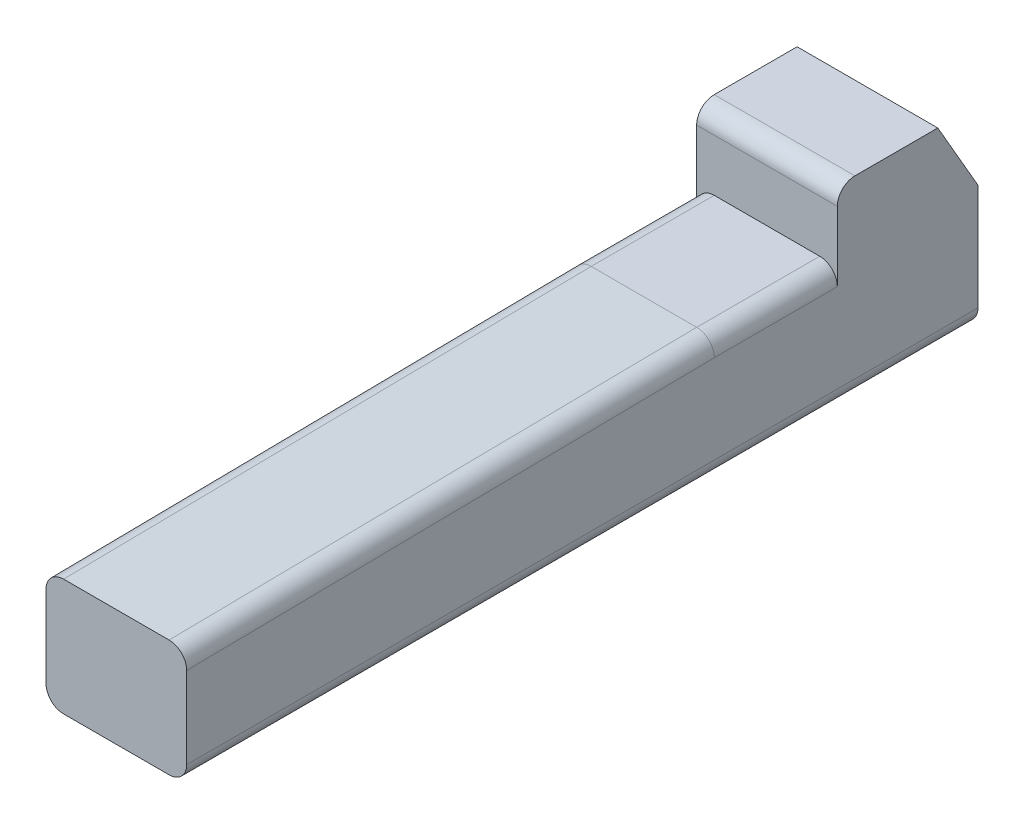
SolidWorks part; units mm, degrees
ref_plane "Front Plane" through (0, 0, 0) normal (0, 0, 1) x (1, 0, 0)
ref_plane "Top Plane" through (0, 0, 0) normal (0, 1, 0) x (1, 0, 0)
ref_plane "Right Plane" through (0, 0, 0) normal (1, 0, 0) x (0, 0, -1)
sketch "Sketch1" plane through (0, 0, 0) normal (0, 0, 1) x (1, 0, 0)
  line L0 (0, 0) -> (0, 4806.0835) construction
  line L1 (0, 0) -> (4806.0835, 0) construction
  line L3 (-4, -5.5) -> (4, -5.5)
  line L4 (-4, -5.5) -> (-4, 5.5)
  line L5 (-4, 5.5) -> (4, 5.5)
  line L6 (4, -5.5) -> (4, 5.5)
  line L7 (-4, -5.5) -> (4, 5.5) construction
  line L8 (-4, 5.5) -> (4, -5.5) construction
  point P5 (0, 0)
  dimension "D1" = 8
  dimension "D2" = 11
extrude "Boss-Extrude1" add sketch "Sketch1" along normal blind 8
sketch "Sketch2" plane through (0, 0, 8) normal (0, 0, 1) x (1, 0, 0)
  line L0 (-4, 1.54) -> (4, 1.54)
  line L4 (4, -5.5) -> (4, 5.5)
  line L5 (4, 5.5) -> (-4, 5.5)
  line L6 (-4, 5.5) -> (-4, -5.5)
  line L7 (-4, -5.5) -> (4, -5.5)
  line L8 (4, -5.5) -> (4, 5.5)
  line L9 (4, 5.5) -> (-4, 5.5)
  line L10 (-4, 5.5) -> (-4, -5.5)
  line L11 (-4, -5.5) -> (4, -5.5)
  line M6 (4, -5.5) -> (4, 5.5)
  line M8 (-4, 5.5) -> (-4, -5.5)
  line M9 (-4, -5.5) -> (4, -5.5)
  dimension "D2" = 7.04
  dimension "D1" = 0
extrude "Boss-Extrude2" add sketch "Sketch2" along normal blind 7 contours L0 M8 M9 M6
sketch "Sketch3" plane through (0, 0, 0) normal (1, 0, 0) x (0, 0, -1)
  line L0 (-15, 1.54) -> (-15, -5.5)
  line L1 (-15, -5.5) -> (-45, -5.5)
  line L2 (-45, -5.5) -> (-45, 1.14)
  line L3 (-45, 1.14) -> (-15, 1.54)
  dimension "D1" = 45
  dimension "D2" = 6.64
extrude "Boss-Extrude3" add sketch "Sketch3" along normal mid plane 8
sketch "Sketch4" plane through (0, 0, 0) normal (1, 0, 0) x (0, 0, -1)
  line L0 (0, -5.5) -> (0, 5.5) construction
  line L1 (-8, 5.5) -> (0, 5.5) construction
  line L2 (0, -5.5) -> (0, 5.5)
  line L3 (-8, 5.5) -> (0, 5.5)
  line L4 (0, 1.54) -> (-2.2863, 5.5)
  point P5 (0, 0)
  point P6 (0, 0)
  point P8 (0, 0)
  dimension "D1" = 30
extrude "Cut-Extrude-Thin1" cut sketch "Sketch4" along normal mid plane 8 thin contours L4
fillet "Fillet1" radius 1 7 edges at (0, 5.5, 8) (-4, 1.54, 11.5) (4, 1.54, 11.5) (4, -5.5, 22.5) (-4, -5.5, 22.5) (-4, 1.34, 30) (4, 1.34, 30)
